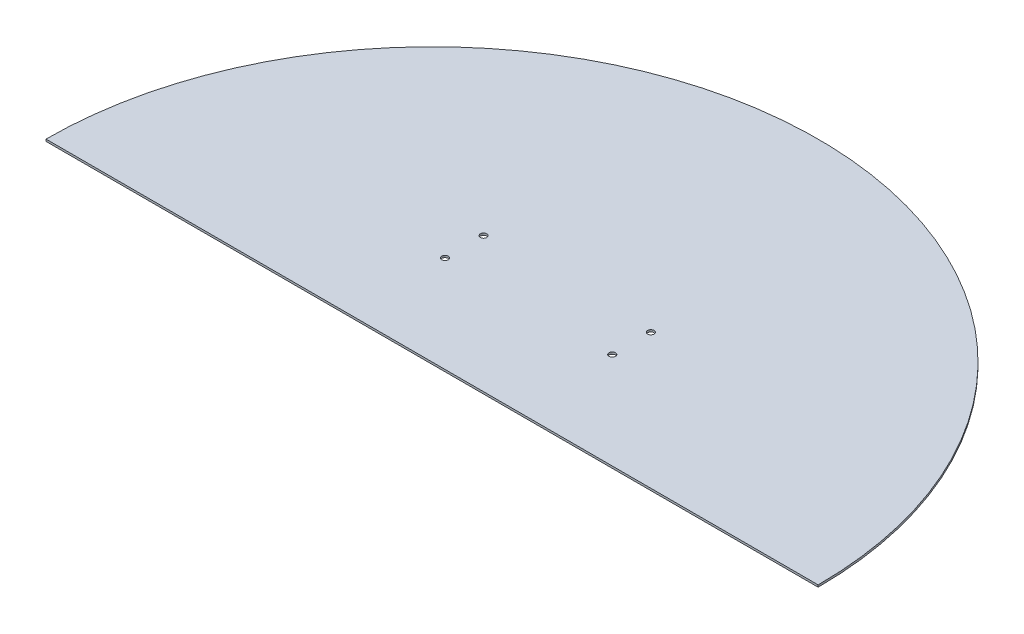
SolidWorks part; units mm, degrees
ref_plane "Front Plane" through (0, 0, 0) normal (0, 0, 1) x (1, 0, 0)
ref_plane "Top Plane" through (0, 0, 0) normal (0, 1, 0) x (1, 0, 0)
ref_plane "Right Plane" through (0, 0, 0) normal (1, 0, 0) x (0, 0, -1)
sketch "Sketch1" plane through (0, 0, 0) normal (0, 1, 0) x (1, 0, 0)
  line L0 (-600, 0) -> (600, 0)
  arc A0 (600, 0) -> (-600, 0) centre (0, 0) ccw
  dimension "D1" = 1200
extrude "Boss-Extrude1" add sketch "Sketch1" along normal blind 3.175
sketch "Sketch2" plane through (0, 3.175, 0) normal (0, 1, 0) x (1, 0, 0)
  line L0 (0, 0) -> (0, 600) construction
  line L1 (-600, 0) -> (600, 0) construction
  line L2 (-130, 210) -> (130, 210)
  line L3 (-130, 210) -> (-130, 150)
  line L4 (-130, 150) -> (130, 150)
  line L5 (130, 210) -> (130, 150)
  line L6 (-130, 210) -> (130, 150) construction
  line L7 (-130, 150) -> (130, 210) construction
  arc A0 (600, 0) -> (-600, 0) centre (0, 0) ccw construction
  circle A1 centre (-130, 210) radius 5
  circle A2 centre (130, 210) radius 5
  circle A3 centre (130, 150) radius 5
  circle A4 centre (-130, 150) radius 5
  point P6 (0, 180)
  point P18 (-131.7509, 150)
  dimension "D4" = 10
  dimension "D1" = 260
  dimension "D2" = 60
  dimension "D3" = 150
extrude "Cut-Extrude1" cut sketch "Sketch2" against normal up to next contours L3 A1 L2 | L2 A1 L3 | L3 A4 L4 | L4 A4 L3 | L5 A3 L4 | L4 A3 L5 | L2 A2 L5 | L5 A2 L2
